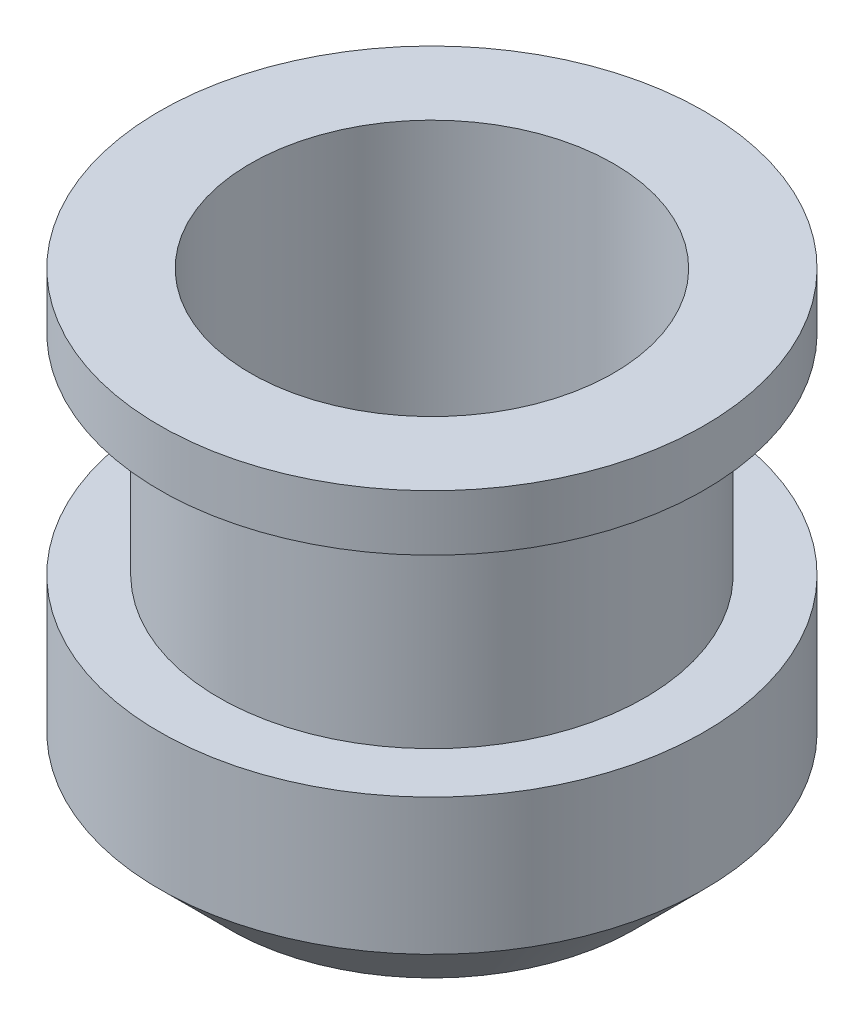
SolidWorks part; units mm, degrees
ref_plane "Front Plane" through (0, 0, 0) normal (0, 0, 1) x (1, 0, 0)
ref_plane "Top Plane" through (0, 0, 0) normal (0, 1, 0) x (1, 0, 0)
ref_plane "Right Plane" through (0, 0, 0) normal (1, 0, 0) x (0, 0, -1)
sketch "Sketch1" plane through (0, 0, 0) normal (0, 0, 1) x (1, 0, 0)
  line L0 (-2.6, 0) -> (-3.9, 0)
  line L1 (-3.9, 0) -> (-3.9, -0.8)
  line L2 (-3.9, -0.8) -> (-3.05, -0.8)
  line L3 (-3.05, -0.8) -> (-3.05, -3.8)
  line L4 (-3.05, -3.8) -> (-3.9, -3.8)
  line L5 (-3.9, -3.8) -> (-3.9, -5.75)
  line L6 (-3.9, -5.75) -> (-2.9, -6.75)
  line L7 (-2.6, -6.75) -> (-2.9, -6.75)
  line L8 (-2.6, -6.75) -> (-2.6, 0)
  line L9 (0, 0) -> (0, 21.6509) construction
  dimension "D1" = 3.9
  dimension "D2" = 0.8
  dimension "D3" = 2.6
  dimension "D4" = 3
  dimension "D5" = 6.75
  dimension "D6" = 1
  dimension "D7" = 3.05
  dimension "D8" = 1
revolve "Revolve1" add sketch "Sketch1" angle 360 about L9
